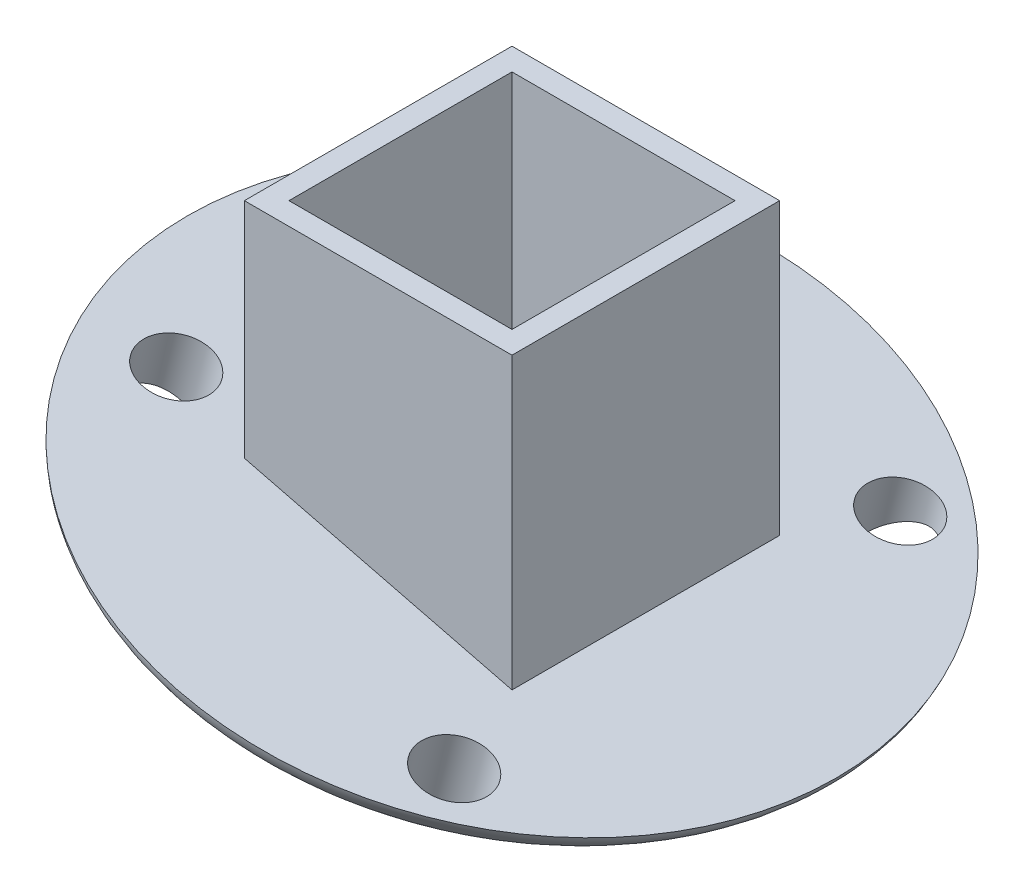
SolidWorks part; units mm, degrees
material "陶瓷"
ref_plane "前视基准面" through (0, 0, 0) normal (0, 0, 1) x (1, 0, 0)
ref_plane "上视基准面" through (0, 0, 0) normal (0, 1, 0) x (1, 0, 0)
ref_plane "右视基准面" through (0, 0, 0) normal (1, 0, 0) x (0, 0, -1)
other "Configuration Table"
sketch "草图1" plane through (0, 0, 0) normal (0, 1, 0) x (1, 0, 0)
  line L1 (-5, -5) -> (5, -5)
  line L2 (-5, -5) -> (-5, 5)
  line L3 (-5, 5) -> (5, 5)
  line L4 (5, -5) -> (5, 5)
  line L5 (-5, -5) -> (5, 5) construction
  line L6 (-5, 5) -> (5, -5) construction
  line L7 (-6, 6) -> (6, 6)
  line L8 (-6, 6) -> (-6, -6)
  line L9 (-6, -6) -> (6, -6)
  line L10 (6, 6) -> (6, -6)
  line L11 (-6, 6) -> (6, -6) construction
  line L12 (-6, -6) -> (6, 6) construction
  point P0 (0, 0)
  point P6 (0, 0)
extrude "凸台-拉伸1" add sketch "草图1" along normal blind 10
sketch "草图2" plane through (6, 0, 0) normal (1, 0, 0) x (0, 0, -1)
  line L0 (-6, 0) -> (6, 0)
  line L1 (6, 0) -> (6, -3)
  line L2 (6, -3) -> (-6, -3)
  line L3 (-6, -3) -> (-6, 0)
extrude "凸台-拉伸2" add sketch "草图2" against normal blind 12
sketch "草图3" plane through (0, 0, 6) normal (0, 0, 1) x (1, 0, 0)
  line L0 (6, -3) -> (6, 0)
  line L1 (6, 10) -> (6, -3) construction
  line L2 (6, 0) -> (-6, 0)
  line L3 (-6, 10) -> (-6, -3) construction
  line L4 (-6, 0) -> (6, -3)
  line L5 (-6, 0) -> (-6, -3)
  line L6 (-6, -3) -> (6, -3)
  line M4 (-6, 10) -> (-6, -3)
  line M5 (-6, -3) -> (6, -3)
extrude "切除-拉伸1" cut sketch "草图3" against normal blind 12 contours L4 M4 M5
ref_plane "基准面1" through (0, 0, 0) normal (0, 0, 1) x (1, 0, 0)
sketch "草图12" plane through (0, 0, 0) normal (0, 0, 1) x (1, 0, 0)
  line L0 (-6, 0) -> (6, -3)
  line L1 (6, -3) -> (0, -1.5)
  line L2 (0, -1.5) -> (14.5521, -5.138)
  line L3 (0, -1.5) -> (-1.2127, -6.3507)
  spline S0 degree 3 poles (-1.2127, -6.3507) (4.8759, -8.1818) (13.5705, -7.2899) (14.5521, -5.138) knots 0 0 0 0 1 1 1 1
revolve "旋转2" add sketch "草图12" angle 360 about L3
sketch "草图13" plane through (-0.3529, -1.4118, 0) normal (0.2425, 0.9701, 0) x (0.9701, -0.2425, 0)
  circle A3 centre (-10, 5) radius 1.5
  circle A4 centre (8, 10) radius 1.5
  circle A5 centre (8, -10) radius 1.5
  circle A6 centre (-10, -5) radius 1.5
  point P0 (4.5053, -10.5244)
extrude "切除-拉伸3" cut sketch "草图13" against normal blind 5
